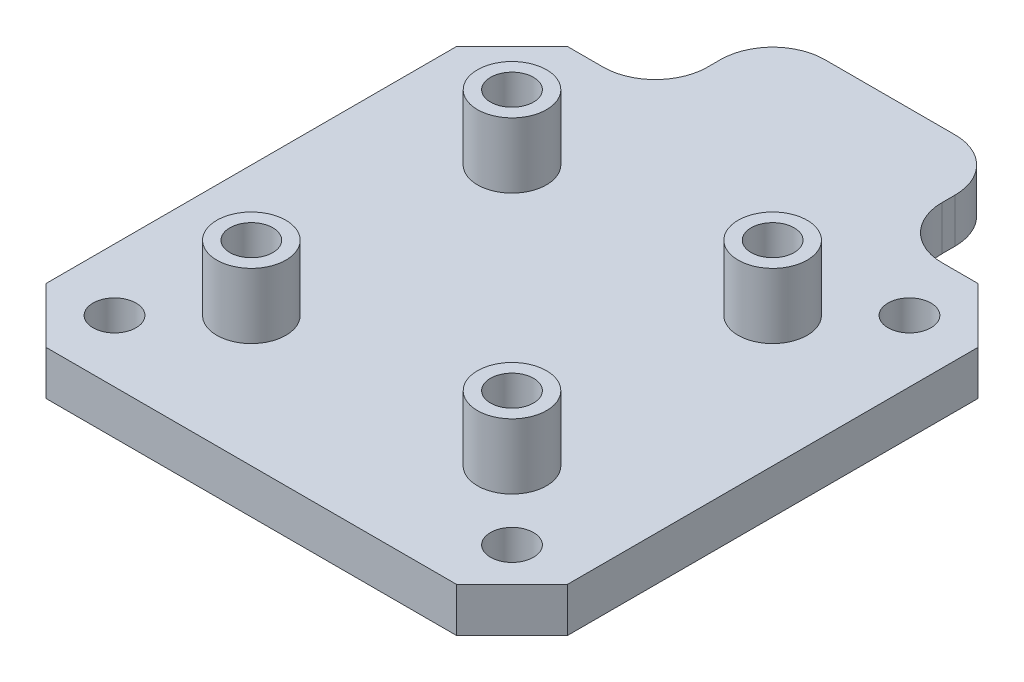
SolidWorks part; units mm, degrees
ref_plane "Front Plane" through (0, 0, 0) normal (0, 0, 1) x (1, 0, 0)
ref_plane "Top Plane" through (0, 0, 0) normal (0, 1, 0) x (1, 0, 0)
ref_plane "Right Plane" through (0, 0, 0) normal (1, 0, 0) x (0, 0, -1)
sketch "Sketch1" plane through (0, 0, 0) normal (0, 1, 0) x (1, 0, 0)
  line L13 (0, -44.7868) -> (0, 44.7868) construction
  line L14 (-20, 20) -> (-13, 20)
  line L15 (-20, 20) -> (-20, -20)
  line L16 (-20, -20) -> (20, -20)
  line L17 (20, 20) -> (20, -20)
  line L18 (-5, 29) -> (5, 29)
  line L19 (-9, 25) -> (-9, 24)
  line L20 (20, 20) -> (13, 20)
  line L21 (9, 25) -> (9, 24)
  line L22 (-44.2539, 0) -> (44.2539, 0) construction
  line L23 (-15.7574, 20) -> (-20, 15.7574)
  line L24 (-20, -15.7574) -> (-15.7574, -20)
  line L25 (20, -15.7574) -> (15.7574, -20)
  line L26 (15.7574, 20) -> (20, 15.7574)
  line L27 (-20, 15.7574) -> (-20, 20)
  line L28 (-20, -15.7574) -> (-20, -20)
  line L29 (20, -15.7574) -> (20, -20)
  arc A0 (-13, 20) -> (-9, 24) centre (-13, 24) ccw
  arc A1 (5, 29) -> (9, 25) centre (5, 25) cw
  arc A2 (-9, 25) -> (-5, 29) centre (-5, 25) cw
  arc A3 (13, 20) -> (9, 24) centre (13, 24) cw
  point P17 (9, 29)
  point P20 (-9, 29)
  point P23 (9, 20)
  dimension "D2" = 4
  dimension "D8" = 4
  dimension "D3" = 40
  dimension "D4" = 20
  dimension "D5" = 20
  dimension "D6" = 18
  dimension "D7" = 9
  dimension "D9" = 45
  dimension "D10" = 45
  dimension "D11" = 6
  dimension "D12" = 9
  dimension "D13" = 40
extrude "Boss-Extrude1" add sketch "Sketch1" along normal mid plane 3.4 contours L20 A3 L21 A1 L18 A2 L19 A0 L14 L23 L15 L24 L16 L25 L17 L26
sketch "Sketch2" plane through (0, 1.7, 0) normal (0, 1, 0) x (1, 0, 0)
  line L0 (-44.2539, 0) -> (44.2539, 0) construction
  line L1 (0, -44.7868) -> (0, 44.7868) construction
  circle A0 centre (-10, 10) radius 1.65
  circle A1 centre (10, 10) radius 1.65
  circle A2 centre (-10, -10) radius 1.65
  circle A3 centre (10, -10) radius 1.65
  circle A4 centre (-15.25, -15.25) radius 1.65
  circle A5 centre (-15.25, 15.25) radius 1.65
  circle A6 centre (15.25, 15.25) radius 1.65
  circle A7 centre (15.25, -15.25) radius 1.65
  dimension "D4" = 20
  dimension "D1" = 3.3
  dimension "D2" = 20
  dimension "D3" = 10
  dimension "D5" = 10
  dimension "D6" = 30.5
  dimension "D7" = 30.5
  dimension "D8" = 15.25
  dimension "D9" = 15.25
extrude "Cut-Extrude1" cut sketch "Sketch2" against normal up to surface (3.4 mm away) up to face at (0, -1.7, -12.25)
sketch "Sketch3" plane through (0, 1.7, 0) normal (0, 1, 0) x (1, 0, 0)
  circle A0 centre (-10, 10) radius 1.65
  circle A1 centre (10, 10) radius 1.65
  circle A2 centre (10, -10) radius 1.65
  circle A3 centre (-10, -10) radius 1.65
  circle A4 centre (-10, 10) radius 2.65
  circle A5 centre (10, 10) radius 2.65
  circle A6 centre (10, -10) radius 2.65
  circle A7 centre (-10, -10) radius 2.65
  dimension "D1" = 5.3
  dimension "D2" = 3.3
extrude "Boss-Extrude2" add sketch "Sketch3" along normal blind 5
sketch "Sketch4" plane through (0, 1.7, 0) normal (0, 1, 0) x (1, 0, 0)
  line L0 (-15.7574, -20) -> (15.7574, -20) construction
  line L1 (-6.7091, 10) -> (-8.3546, 12.85)
  line L2 (-8.3546, 12.85) -> (-11.6454, 12.85)
  line L3 (-11.6454, 12.85) -> (-13.2909, 10)
  line L4 (-13.2909, 10) -> (-11.6454, 7.15)
  line L5 (-11.6454, 7.15) -> (-8.3546, 7.15)
  line L6 (-8.3546, 7.15) -> (-6.7091, 10)
  line L7 (13.2909, 10) -> (11.6454, 12.85)
  line L8 (11.6454, 12.85) -> (8.3546, 12.85)
  line L9 (8.3546, 12.85) -> (6.7091, 10)
  line L10 (6.7091, 10) -> (8.3546, 7.15)
  line L11 (8.3546, 7.15) -> (11.6454, 7.15)
  line L12 (11.6454, 7.15) -> (13.2909, 10)
  line L13 (13.2909, -10) -> (11.6454, -7.15)
  line L14 (11.6454, -7.15) -> (8.3546, -7.15)
  line L15 (8.3546, -7.15) -> (6.7091, -10)
  line L16 (6.7091, -10) -> (8.3546, -12.85)
  line L17 (8.3546, -12.85) -> (11.6454, -12.85)
  line L18 (11.6454, -12.85) -> (13.2909, -10)
  line L19 (-6.7091, -10) -> (-8.3546, -7.15)
  line L20 (-8.3546, -7.15) -> (-11.6454, -7.15)
  line L21 (-11.6454, -7.15) -> (-13.2909, -10)
  line L22 (-13.2909, -10) -> (-11.6454, -12.85)
  line L23 (-11.6454, -12.85) -> (-8.3546, -12.85)
  line L24 (-8.3546, -12.85) -> (-6.7091, -10)
  circle A0 centre (-10, 10) radius 2.85 construction
  circle A1 centre (10, 10) radius 2.85 construction
  circle A2 centre (10, -10) radius 2.85 construction
  circle A3 centre (-10, -10) radius 2.85 construction
  dimension "D1" = 5.7
extrude "Cut-Extrude2" cut sketch "Sketch4" against normal blind 2.4 from offset 0.5
equation "\"Width\"=40"
equation "\"D3@Sketch1\"=\"Width\""
equation "\"D4@Sketch1\"=\"Width\"/2"
equation "\"D5@Sketch1\"=\"Width\"/2"
equation "\"D13@Sketch1\"=\"Width\""
equation "\"HoleSize\"= 3.3"
equation "\"D1@Sketch2\"=\"HoleSize\""
equation "\"InnerHoleDist\"=20"
equation "\"D2@Sketch2\"=\"InnerHoleDist\""
equation "\"D3@Sketch2\"=\"InnerHoleDist\"/2"
equation "\"D4@Sketch2\"=\"InnerHoleDist\""
equation "\"D5@Sketch2\"=\"InnerHoleDist\"/2"
equation "\"OutHoleDist\"=30.5"
equation "\"D6@Sketch2\"=\"OutHoleDist\""
equation "\"D7@Sketch2\"=\"OutHoleDist\""
equation "\"D8@Sketch2\"=\"OutHoleDist\"/2"
equation "\"D9@Sketch2\"=\"OutHoleDist\"/2"
equation "\"D2@Sketch3\"=\"HoleSize\""
